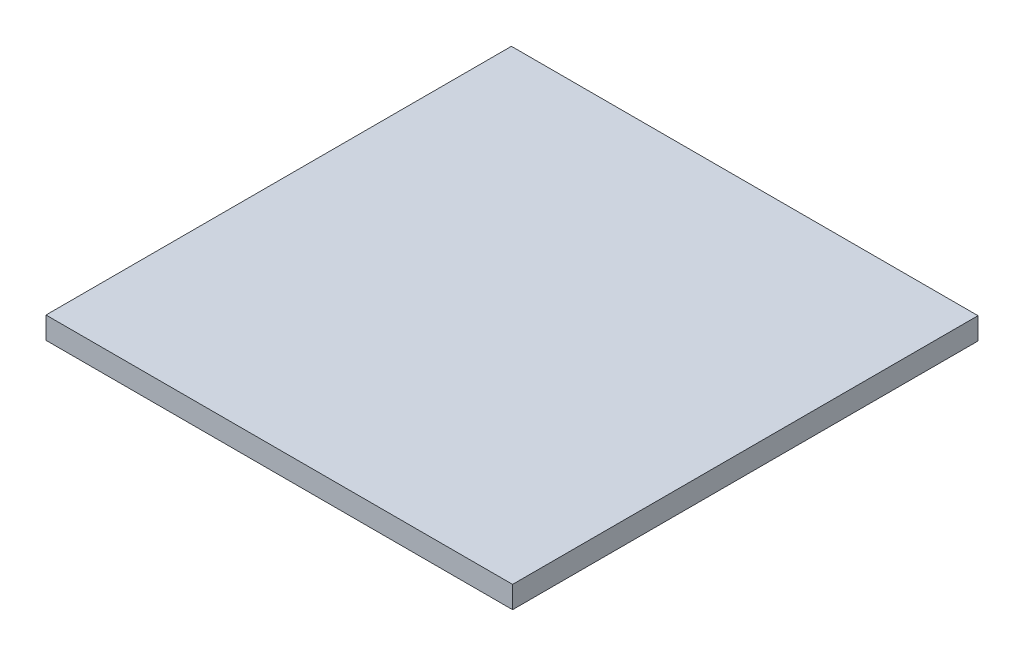
SolidWorks part; units mm, degrees
ref_plane "Front Plane" through (0, 0, 0) normal (0, 0, 1) x (1, 0, 0)
ref_plane "Top Plane" through (0, 0, 0) normal (0, 1, 0) x (1, 0, 0)
ref_plane "Right Plane" through (0, 0, 0) normal (1, 0, 0) x (0, 0, -1)
sketch "Sketch1" plane through (0, 0, 0) normal (0, 1, 0) x (1, 0, 0)
  line L1 (0, 0) -> (-637.6, 0)
  line L2 (0, 0) -> (0, 636)
  line L3 (0, 636) -> (-637.6, 636)
  line L4 (-637.6, 0) -> (-637.6, 636)
  dimension "D1" = 637.6
  dimension "D2" = 636
extrude "Boss-Extrude1" add sketch "Sketch1" along normal blind 30 contours L2 L1 L4 L3
